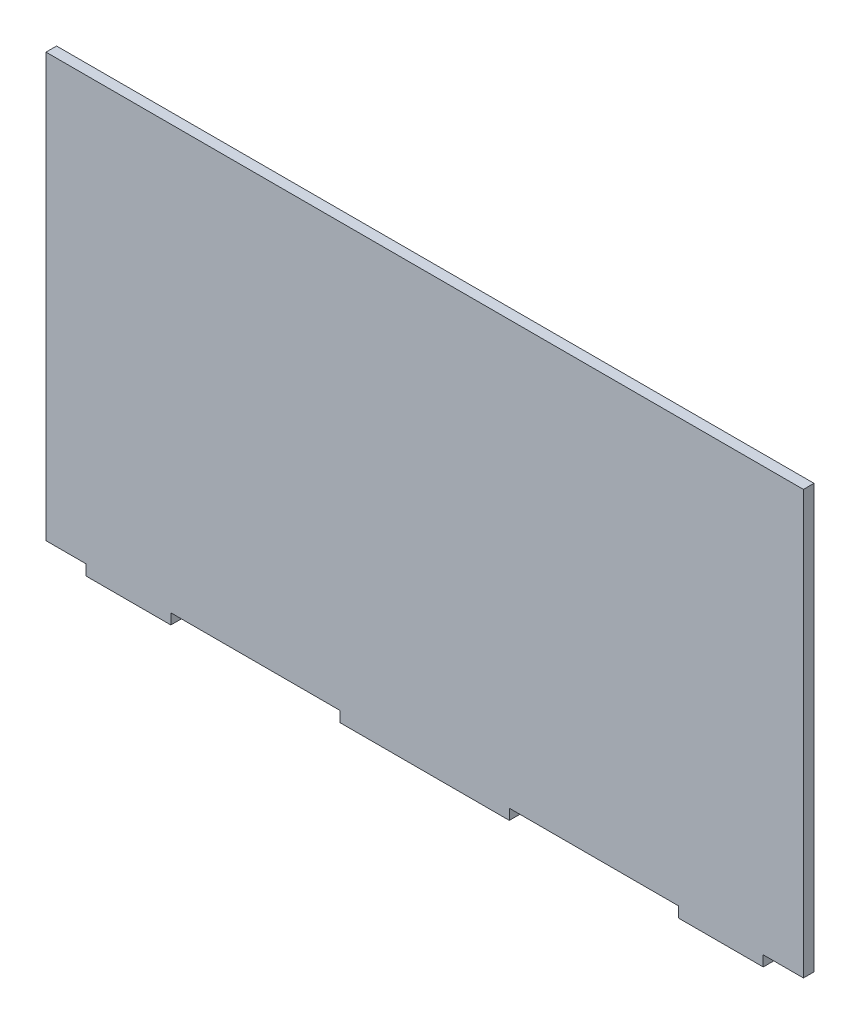
SolidWorks part; units mm, degrees
material "Plastique personnalisé"
ref_plane "Plan de face" through (0, 0, 0) normal (0, 0, 1) x (1, 0, 0)
ref_plane "Plan de dessus" through (0, 0, 0) normal (0, 1, 0) x (1, 0, 0)
ref_plane "Plan de droite" through (0, 0, 0) normal (1, 0, 0) x (0, 0, -1)
sketch "Esquisse1" plane through (0, 0, 0) normal (0, 0, 1) x (1, 0, 0)
  line L0 (-10.8986, 0.8167) -> (8.1014, 0.8167)
  line L1 (8.1014, 0.8167) -> (8.1014, -4.1833)
  line L2 (8.1014, -4.1833) -> (48.1014, -4.1833)
  line L3 (48.1014, -4.1833) -> (48.1014, 0.8167)
  line L4 (48.1014, 0.8167) -> (128.1014, 0.8167)
  line L5 (128.1014, 0.8167) -> (128.1014, -4.1833)
  line L6 (128.1014, -4.1833) -> (208.1014, -4.1833)
  line L7 (208.1014, -4.1833) -> (208.1014, 0.8167)
  line L8 (208.1014, 0.8167) -> (288.1014, 0.8167)
  line L9 (288.1014, 0.8167) -> (288.1014, -4.1833)
  line L10 (288.1014, -4.1833) -> (328.1014, -4.1833)
  line L11 (328.1014, -4.1833) -> (328.1014, 0.8167)
  line L12 (328.1014, 0.8167) -> (347.1014, 0.8167)
  line L16 (-10.8986, 0.8167) -> (-10.8986, 200.8167)
  line L17 (-10.8986, 200.8167) -> (347.1014, 200.8167)
  line L18 (347.1014, 200.8167) -> (347.1014, 0.8167)
  dimension "D1" = 19
  dimension "D2" = 19
  dimension "D3" = 40
  dimension "D4" = 40
  dimension "D5" = 80
  dimension "D6" = 80
  dimension "D7" = 80
  dimension "D8" = 5
  dimension "D9" = 5
  dimension "D10" = 5
  dimension "D11" = 5
  dimension "D12" = 5
  dimension "D13" = 5
  dimension "D14" = 200
extrude "Boss.-Extru.1" add sketch "Esquisse1" along normal blind 5
